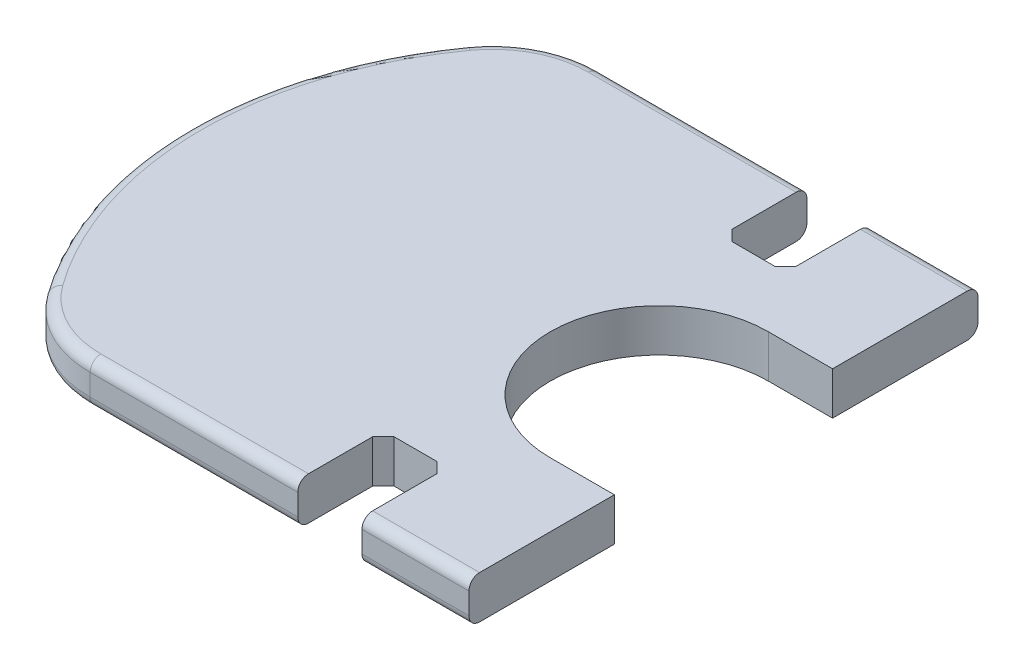
SolidWorks part; units mm, degrees
ref_plane "Front" through (0, 0, 0) normal (0, 0, 1) x (1, 0, 0)
ref_plane "Top" through (0, 0, 0) normal (0, 1, 0) x (1, 0, 0)
ref_plane "Right" through (0, 0, 0) normal (1, 0, 0) x (0, 0, -1)
sketch "Sketch1" plane through (0, 0, 0) normal (0, 1, 0) x (1, 0, 0)
  line L0 (0, 5.1) -> (3, 5.1)
  line L1 (3, 5.1) -> (3, 11.9)
  line L2 (3, 11.9) -> (-17, 11.9)
  line L3 (-4.431, 0) -> (4.4172, 0) construction
  line L4 (0, -5.1) -> (3, -5.1)
  line L5 (3, -5.1) -> (3, -11.9)
  line L6 (3, -11.9) -> (-17, -11.9)
  circle A0 centre (0, 0) radius 5.1 construction
  arc A1 (0, 5.1) -> (0, -5.1) centre (0, 0) ccw
  arc A4 (-17, 11.9) -> (-17, -11.9) centre (-5.1, 0) ccw
extrude "Boss-Extrude1" add sketch "Sketch1" along normal blind 2
fillet "Fillet2" radius 5 2 edges at (-17, 1, 11.9) (-17, 1, -11.9)
fillet "Fillet1" radius 0.5 10 edges at (-5.8541, 0, -11.9) (-5.8541, 0, 11.9) (-5.8541, 2, -11.9) (-5.8541, 2, 11.9) (-21.9291, 0, 0) (-21.9291, 2, 0) (-16.9905, 0, 11.3487) (-16.9905, 0, -11.3487) (-16.9905, 2, 11.3487) (-16.9905, 2, -11.3487)
sketch "Sketch2" plane through (0, 2, 0) normal (0, 1, 0) x (1, 0, 0)
  line L0 (-5, 15.7403) -> (-5, -15.6489) construction
  line L1 (3, 5.1) -> (3, 11.4) construction
  line L2 (-5, 14.9) -> (-5, 7.9)
  line L3 (-5, 7.9) -> (-2, 7.9)
  line L4 (-2, 7.9) -> (-2, 14.9)
  line L5 (-2, 14.9) -> (-5, 14.9)
  line L6 (-14.7083, 11.9) -> (3, 11.9) construction
  line L7 (0, 0) -> (-30.7004, 0) construction
  line L8 (-2, -7.9) -> (-2, -14.9)
  line L9 (-5, -7.9) -> (-2, -7.9)
  line L10 (-5, -14.9) -> (-5, -7.9)
  line L11 (-2, -14.9) -> (-5, -14.9)
  dimension "D1" = 8
  dimension "D2" = 3
extrude "Cut-Extrude1" cut sketch "Sketch2" against normal blind 10
chamfer "Chamfer1" distance 0.5 angle 45 4 edges at (-2, 1, 7.9) (-5, 1, 7.9) (-2, 1, -7.9) (-5, 1, -7.9)
